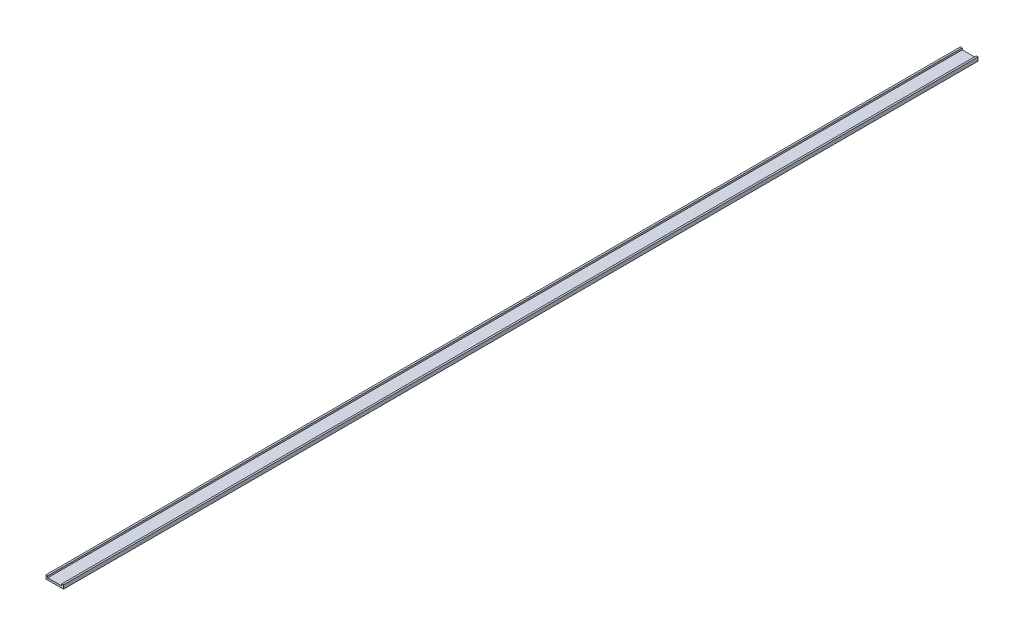
SolidWorks part; units mm, degrees
ref_plane "前视基准面" through (0, 0, 0) normal (0, 0, 1) x (1, 0, 0)
ref_plane "上视基准面" through (0, 0, 0) normal (0, 1, 0) x (1, 0, 0)
ref_plane "右视基准面" through (0, 0, 0) normal (1, 0, 0) x (0, 0, -1)
sketch "草图1" plane through (0, 0, 0) normal (0, 0, 1) x (1, 0, 0)
  line L0 (15, 0) -> (-15, 0)
  line L1 (-15, 0) -> (-15, 6.5)
  line L2 (-15, 6.5) -> (-12, 6.5)
  line L3 (-12, 6.5) -> (-12, 3.5)
  line L4 (-12, 3.5) -> (12, 3.5)
  line L5 (0, 13.656) -> (0, 0) construction
  line L6 (12, 6.5) -> (12, 3.5)
  line L7 (15, 6.5) -> (12, 6.5)
  line L8 (15, 0) -> (15, 6.5)
  point P9 (0, 3.5)
  dimension "D1" = 30
  dimension "D2" = 6.5
  dimension "D3" = 3
  dimension "D4" = 3
extrude "凸台-拉伸1" add sketch "草图1" along normal blind 1570
